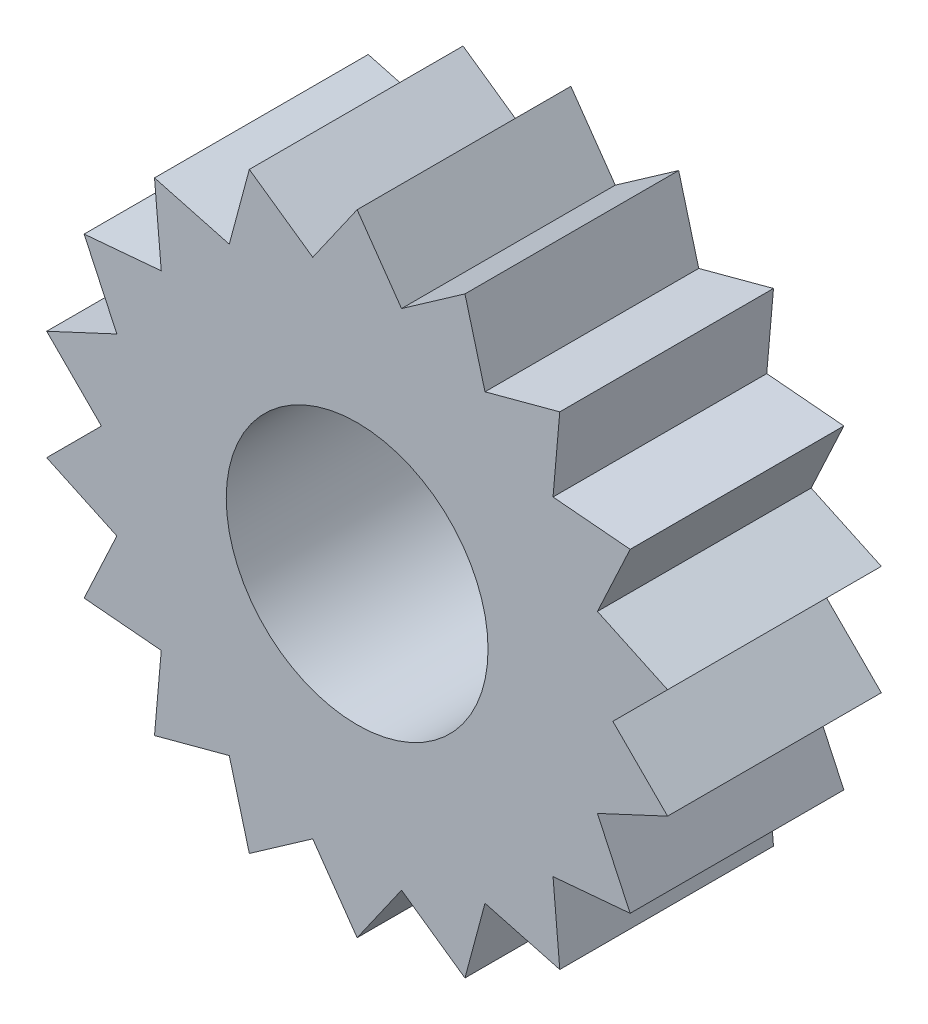
SolidWorks part; units mm, degrees
ref_plane "Ebene vorne" through (0, 0, 0) normal (0, 0, 1) x (1, 0, 0)
ref_plane "Ebene oben" through (0, 0, 0) normal (0, 1, 0) x (1, 0, 0)
ref_plane "Ebene rechts" through (0, 0, 0) normal (1, 0, 0) x (0, 0, -1)
sketch "Skizze1" plane through (0, 0, 0) normal (0, 0, 1) x (1, 0, 0)
  circle A0 centre (0, 0) radius 5.9
  dimension "D1" = 11.8
extrude "Aufsatz-Linear austragen1" add sketch "Skizze1" along normal blind 4
sketch "Skizze2" plane through (0, 0, 0) normal (0, 0, -1) x (-1, 0, 0)
  circle A0 centre (0, 0) radius 2.45
  dimension "D1" = 4.9
extrude "Schnitt-Linear austragen1" cut sketch "Skizze2" against normal blind 4
sketch "Skizze3" plane through (0, 0, 0) normal (0, 0, -1) x (-1, 0, 0)
  line L0 (0, 0) -> (0, 5.6694) construction
  line L1 (0, 0) -> (0.9716, 5.5102) construction
  line L2 (0, 5.9) -> (0.8311, 4.7131)
  line L3 (2.0179, 5.5442) -> (0.8311, 4.7131)
  line L4 (2.0179, 5.5442) -> (2.3929, 4.1447)
  line L5 (3.7924, 4.5197) -> (2.3929, 4.1447)
  line L6 (3.7924, 4.5197) -> (3.6662, 3.0763)
  line L7 (5.1095, 2.95) -> (3.6662, 3.0763)
  line L8 (5.1095, 2.95) -> (4.4972, 1.6369)
  line L9 (5.8104, 1.0245) -> (4.4972, 1.6369)
  line L10 (5.8104, 1.0245) -> (4.7858, 0)
  line L11 (5.8104, -1.0245) -> (4.7858, 0)
  line L12 (5.8104, -1.0245) -> (4.4972, -1.6369)
  line L13 (5.1095, -2.95) -> (4.4972, -1.6369)
  line L14 (5.1095, -2.95) -> (3.6662, -3.0763)
  line L15 (3.7924, -4.5197) -> (3.6662, -3.0763)
  line L16 (3.7924, -4.5197) -> (2.3929, -4.1447)
  line L17 (2.0179, -5.5442) -> (2.3929, -4.1447)
  line L18 (2.0179, -5.5442) -> (0.8311, -4.7131)
  line L19 (0, -5.9) -> (0.8311, -4.7131)
  line L20 (0, -5.9) -> (-0.8311, -4.7131)
  line L21 (-2.0179, -5.5442) -> (-0.8311, -4.7131)
  line L22 (-2.0179, -5.5442) -> (-2.3929, -4.1447)
  line L23 (-3.7924, -4.5197) -> (-2.3929, -4.1447)
  line L24 (-3.7924, -4.5197) -> (-3.6662, -3.0763)
  line L25 (-5.1095, -2.95) -> (-3.6662, -3.0763)
  line L26 (-5.1095, -2.95) -> (-4.4972, -1.6369)
  line L27 (-5.8104, -1.0245) -> (-4.4972, -1.6369)
  line L28 (-5.8104, -1.0245) -> (-4.7858, 0)
  line L29 (-5.8104, 1.0245) -> (-4.7858, 0)
  line L30 (-5.8104, 1.0245) -> (-4.4972, 1.6369)
  line L31 (-5.1095, 2.95) -> (-4.4972, 1.6369)
  line L32 (-5.1095, 2.95) -> (-3.6662, 3.0763)
  line L33 (-3.7924, 4.5197) -> (-3.6662, 3.0763)
  line L34 (-3.7924, 4.5197) -> (-2.3929, 4.1447)
  line L35 (-2.0179, 5.5442) -> (-2.3929, 4.1447)
  line L36 (-2.0179, 5.5442) -> (-0.8311, 4.7131)
  line L37 (0, 5.9) -> (-0.8311, 4.7131)
  circle A1 centre (0, 0) radius 5.9 construction
  circle A2 centre (0, 0) radius 6.9159
  point P14 (0, 0)
  point P64 (0, 0)
  dimension "D1" = 10
  dimension "D2" = 45
  dimension "D3" = 18
extrude "Schnitt-Linear austragen3" cut sketch "Skizze3" against normal blind 6
